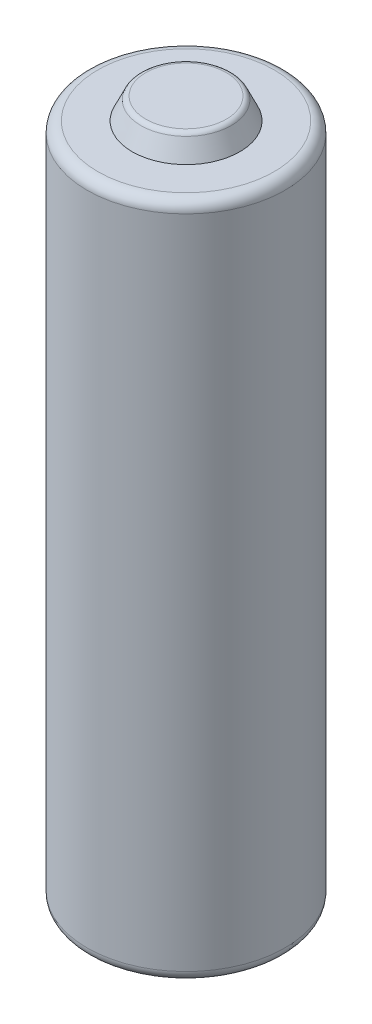
SolidWorks part; units mm, degrees
ref_plane "Front Plane" through (0, 0, 0) normal (0, 0, 1) x (1, 0, 0)
ref_plane "Top Plane" through (0, 0, 0) normal (0, 1, 0) x (1, 0, 0)
ref_plane "Right Plane" through (0, 0, 0) normal (1, 0, 0) x (0, 0, -1)
sketch "Sketch1" plane through (0, 0, 0) normal (0, 1, 0) x (1, 0, 0)
  circle A0 centre (0, 0) radius 9.2
  dimension "D1" = 18.4
extrude "Boss-Extrude1" add sketch "Sketch1" along normal blind 63
sketch "Sketch2" plane through (0, 63, 0) normal (0, 1, 0) x (1, 0, 0)
  circle A0 centre (0, 0) radius 4.9974
extrude "Boss-Extrude2" add sketch "Sketch2" along normal blind 2 draft 25
sketch "Sketch3" plane through (0, 0, 0) normal (0, -1, 0) x (1, 0, 0)
  circle A0 centre (0, 0) radius 7.0017
  circle A1 centre (0, 0) radius 6.0044
extrude "Cut-Extrude1" cut sketch "Sketch3" against normal blind 3 draft 25
fillet "Fillet1" radius 1 1 edges at (0, 63, 9.2)
fillet "Fillet2" radius 0.5 1 edges at (0, 65, 4.0648)
fillet "Fillet3" radius 1 1 edges at (0, 0, 9.2)
